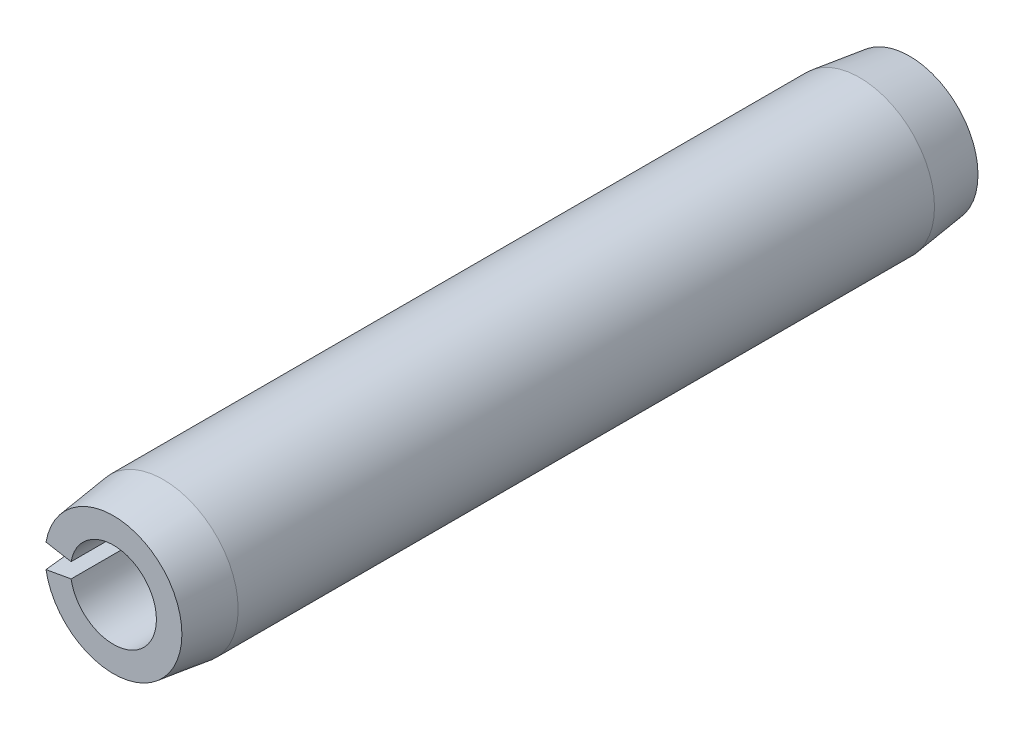
SolidWorks part; units mm, degrees
ref_plane "Front Plane" through (0, 0, 0) normal (0, 0, 1) x (1, 0, 0)
ref_plane "Top Plane" through (0, 0, 0) normal (0, 1, 0) x (1, 0, 0)
ref_plane "Right Plane" through (0, 0, 0) normal (1, 0, 0) x (0, 0, -1)
sketch "Sketch5" plane through (0, 0, 0) normal (0, 0, 1) x (1, 0, 0)
  line L0 (1.3716, 0) -> (2.3876, 0) construction
  line L1 (-2.3513, 0.4146) -> (-1.3508, 0.2382)
  line L2 (-1.3508, -0.2382) -> (-2.3513, -0.4146)
  arc A0 (-2.3513, -0.4146) -> (-2.3513, 0.4146) centre (0, 0) ccw
  arc A1 (-1.3508, -0.2382) -> (-1.3508, 0.2382) centre (0, 0) ccw
  circle A2 centre (0, 0) radius 2.3876 construction
  dimension "Diameter" = 4.7752
  dimension "Wall Thickness" = 1.016
  dimension "Opening Angle" = 20
sketch "Sketch6" plane through (0, 0, 0) normal (1, 0, 0) x (0, 0, -1)
  line L0 (12.7, 0) -> (-12.7, 0) construction
  line L1 (0, 2.3876) -> (0, -2.3876) construction
  line L4 (0, 2.3876) -> (0, -2.3876) construction
  line L5 (12.7, 0) -> (12.7, 2.3876) construction
  line L6 (12.7, 2.3876) -> (-12.7, 2.3876) construction
  line L7 (-12.7, 2.3876) -> (-12.7, 0) construction
  line L8 (12.7, 2.1844) -> (11.1083, 2.3876)
  dimension "Length" = 25.4
  dimension "Chamfer" = 1.5917
  dimension "D1" = 0.2032
sketch "Sketch1" plane through (0, 0, 0) normal (0, 0, 1) x (1, 0, 0)
  line L1 (-1.3508, -0.2382) -> (-2.3513, -0.4146) construction
  line L2 (-2.3513, 0.4146) -> (-1.3508, 0.2382) construction
  line L3 (-1.3508, -0.2382) -> (-2.3513, -0.4146)
  line L4 (-2.3513, 0.4146) -> (-1.3508, 0.2382)
  arc A2 (-2.3513, -0.4146) -> (-2.3513, 0.4146) centre (0, 0) ccw construction
  arc A3 (-1.3508, -0.2382) -> (-1.3508, 0.2382) centre (0, 0) ccw construction
  arc A4 (-2.3513, -0.4146) -> (-2.3513, 0.4146) centre (0, 0) ccw
  arc A5 (-1.3508, -0.2382) -> (-1.3508, 0.2382) centre (0, 0) ccw
extrude "Extrude1" add sketch "Sketch1" against normal up to vertex (12.7 mm away) and the other way up to vertex (12.7 mm away) up to point (0, 2.3876, -12.7) other way up to point (0, 2.3876, 12.7)
sketch "Sketch2" plane through (0, 0, 0) normal (1, 0, 0) x (0, 0, -1)
  line L0 (12.7, 2.1844) -> (11.1083, 2.3876)
  line L1 (11.1083, 2.3876) -> (12.7, 2.3876)
  line L4 (12.7, 2.3876) -> (12.7, 2.1844)
revolve "Cut-Revolve1" cut sketch "Sketch2" angle 360 about L0
mirror "Mirror1" about plane through (0, 0, 0) normal (0, 0, 1) of "Cut-Revolve1"
equation "\"D1@Sketch6\"=\"Wall Thickness@Sketch5\"*.2"
equation "\"Chamfer@Sketch6\"=\"Diameter@Sketch5\"/3"
